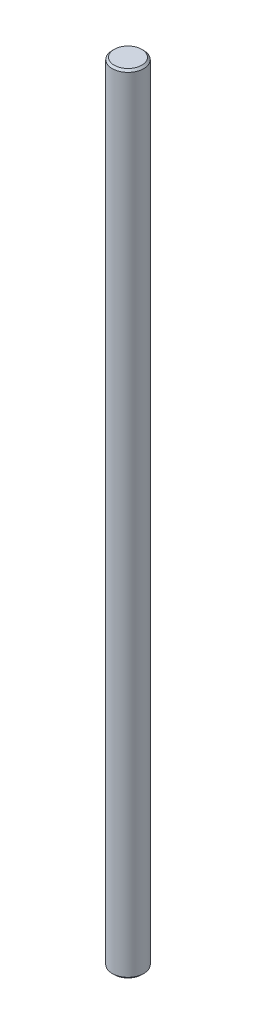
SolidWorks part; units mm, degrees
ref_plane "Спереди" through (0, 0, 0) normal (0, 0, 1) x (1, 0, 0)
ref_plane "Сверху" through (0, 0, 0) normal (0, 1, 0) x (1, 0, 0)
ref_plane "Справа" through (0, 0, 0) normal (1, 0, 0) x (0, 0, -1)
sketch "Эскиз1" plane through (0, 0, 0) normal (0, 1, 0) x (1, 0, 0)
  circle A0 centre (0, 0) radius 4
  dimension "D1" = 8
extrude "Бобышка-Вытянуть1" add sketch "Эскиз1" along normal blind 200
chamfer "Фаска1" distance 0.5 angle 45 2 edges at (0, 200, 4) (0, 0, 4)
